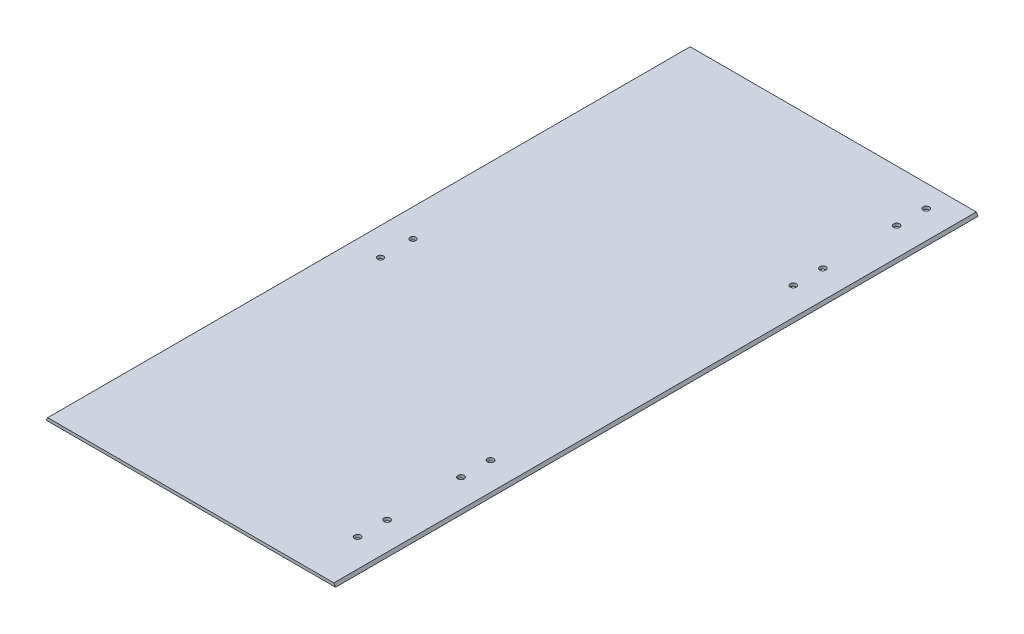
SolidWorks part; units mm, degrees
ref_plane "前视基准面" through (0, 0, 0) normal (0, 0, 1) x (1, 0, 0)
ref_plane "上视基准面" through (0, 0, 0) normal (0, 1, 0) x (1, 0, 0)
ref_plane "右视基准面" through (0, 0, 0) normal (1, 0, 0) x (0, 0, -1)
other "Configuration Table"
sketch "草图2" plane through (0, 0, 0) normal (0, 0, 1) x (1, 0, 0)
  line L0 (-98, -1) -> (-96.8453, 1)
  line L1 (-98, -1) -> (98.07, -1)
  line L3 (-96.8453, 1) -> (96.9153, 1)
  line L5 (-98, -1) -> (96.9217, 0.989) construction
  line L6 (-96.8525, 0.9876) -> (98.07, -1) construction
  line L7 (98.07, -1) -> (96.9153, 1)
  point P0 (0, 0)
  dimension "D1" = 60
  dimension "D2" = 196.07
  dimension "D3" = 60
  dimension "D4" = 2
  dimension "D5" = 1
extrude "凸台-拉伸1" add sketch "草图2" against normal blind 435
sketch "草图3" plane through (0, -1, 0) normal (0, -1, 0) x (-1, 0, 0)
  line L1 (98, 435) -> (98, 0) construction
  line L2 (0, 0) -> (0, 458.5279) construction
  line L3 (98, 217.5) -> (-98.07, 217.5) construction
  line L4 (-98.07, 435) -> (-98.07, 0) construction
  circle A12 centre (-78, 35) radius 2.1
  circle A13 centre (-78, 55) radius 2.1
  circle A14 centre (-78, 105) radius 2.1
  circle A15 centre (-78, 125) radius 2.1
  circle A16 centre (-78, 330) radius 2.1
  circle A17 centre (-78, 350) radius 2.1
  circle A18 centre (-78, 400) radius 2.1
  circle A19 centre (-78, 420) radius 2.1
extrude "切除-拉伸1" cut sketch "草图3" against normal through all
sketch "草图5" plane through (0, -1, 0) normal (0, -1, 0) x (1, 0, 0)
  line L0 (0, 0) -> (0.035, -435) construction
  line L1 (-98, -435) -> (98.07, -435) construction
  line L2 (-98, -217.5) -> (98.07, -217.5) construction
  line L3 (-98, -435) -> (-98, 0) construction
  line L4 (98.07, -435) -> (98.07, 0) construction
sketch "草图6" plane through (0, -1, 0) normal (0, -1, 0) x (-1, 0, 0)
  line L0 (98, 435) -> (98, 0) construction
  line L1 (98, 217.5) -> (-98.07, 217.5) construction
  circle A0 centre (78, 206.5) radius 2
  circle A1 centre (78, 228.5) radius 2
  dimension "D1" = 20
  dimension "D2" = 11
extrude "切除-拉伸2" cut sketch "草图6" against normal through all
